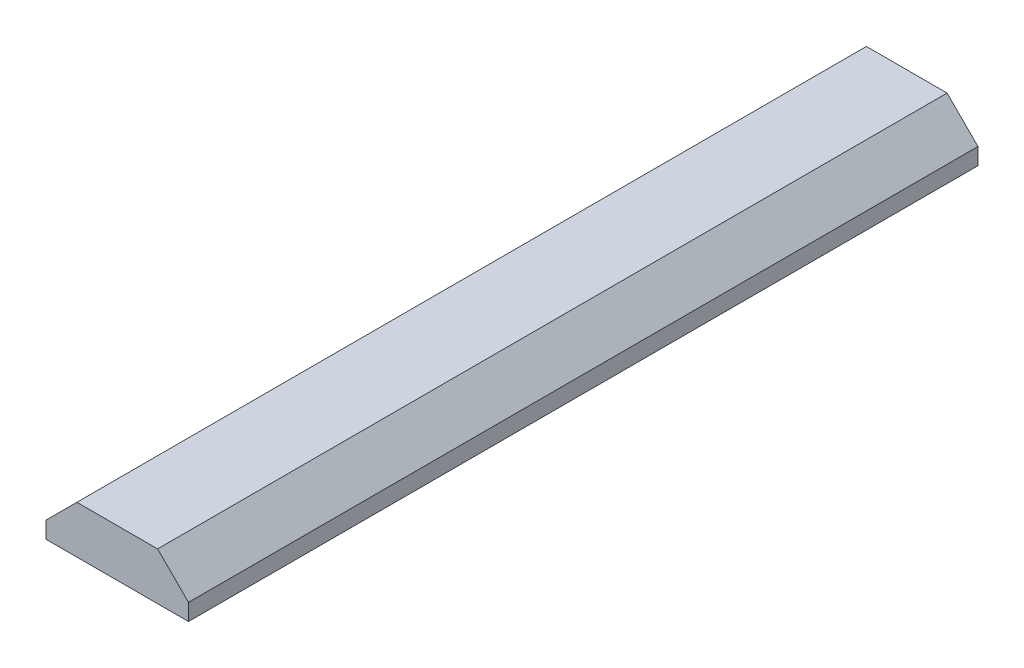
SolidWorks part; units mm, degrees
ref_plane "Ebene vorne" through (0, 0, 0) normal (0, 0, 1) x (1, 0, 0)
ref_plane "Ebene oben" through (0, 0, 0) normal (0, 1, 0) x (1, 0, 0)
ref_plane "Ebene rechts" through (0, 0, 0) normal (1, 0, 0) x (0, 0, -1)
sketch "Skizze1" plane through (0, 0, 0) normal (0, 0, 1) x (1, 0, 0)
  line L0 (0, 0) -> (0, 23680.6173) construction
  line L1 (3.4, 1.8089) -> (-3.4, 1.8089)
  line L2 (-3.4, 1.8089) -> (-6, -0.7911)
  line L3 (-6, -0.7911) -> (-6, -2.1911)
  line L4 (-6, -2.1911) -> (6, -2.1911)
  line L5 (6, -0.7911) -> (6, -2.1911)
  line L6 (3.4, 1.8089) -> (6, -0.7911)
  point P9 (0, -2.1911)
  point P11 (0, 1.8089)
  dimension "D1" = 3.4
  dimension "D2" = 6
  dimension "D3" = 4
  dimension "D4" = 135
extrude "Aufsatz-Linear austragen1" add sketch "Skizze1" along normal blind 66.5 contours L1 L2 L3 L4 L5 L6
